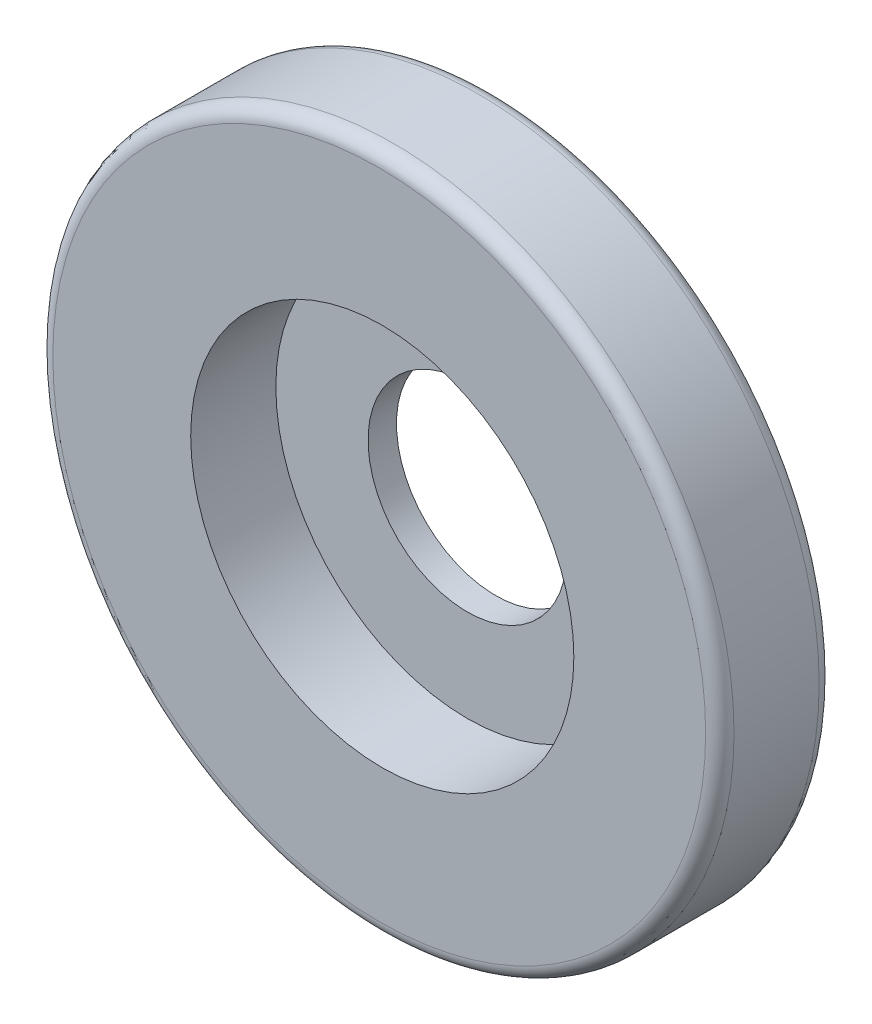
SolidWorks part; units mm, degrees
ref_plane "Front Plane" through (0, 0, 0) normal (0, 0, 1) x (1, 0, 0)
ref_plane "Top Plane" through (0, 0, 0) normal (0, 1, 0) x (1, 0, 0)
ref_plane "Right Plane" through (0, 0, 0) normal (1, 0, 0) x (0, 0, -1)
sketch "Sketch1" plane through (0, 0, 0) normal (0, 0, 1) x (1, 0, 0)
  circle A0 centre (0, 0) radius 1.75
  circle A1 centre (-0.0535, 0) radius 6
  dimension "D1" = 3.5
  dimension "D2" = 12
extrude "Boss-Extrude1" add sketch "Sketch1" along normal blind 0.5
sketch "Sketch2" plane through (0, 0, 0.5) normal (0, 0, 1) x (1, 0, 0)
  circle A0 centre (0, 0) radius 3.375
  circle A1 centre (-0.0535, 0) radius 6 construction
  circle A2 centre (-0.0535, 0) radius 6
  dimension "D1" = 6.75
extrude "Boss-Extrude2" add sketch "Sketch2" along normal blind 1.5
fillet "Fillet1" radius 0.25 2 edges at (5.9465, 0, 2) (5.9465, 0, 0)
